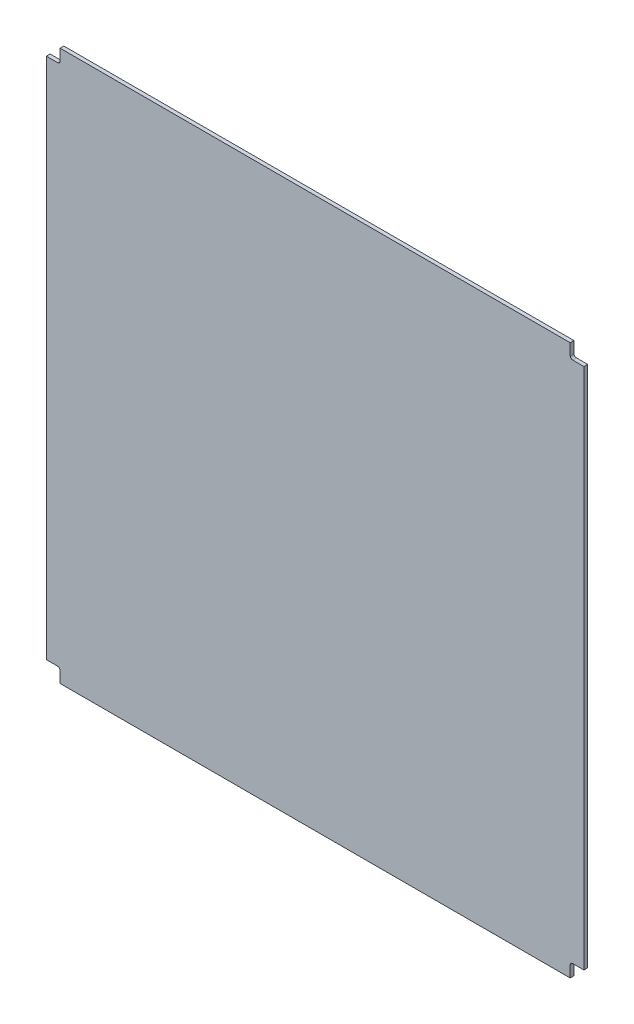
SolidWorks part; units mm, degrees
ref_plane "Front Plane" through (0, 0, 0) normal (0, 0, 1) x (1, 0, 0)
ref_plane "Top Plane" through (0, 0, 0) normal (0, 1, 0) x (1, 0, 0)
ref_plane "Right Plane" through (0, 0, 0) normal (1, 0, 0) x (0, 0, -1)
sketch "Sketch1" plane through (0, 0, 0) normal (0, 0, 1) x (1, 0, 0)
  line L0 (0, 427.6735) -> (0, 0) construction
  line L1 (0, 0) -> (427.6735, 0) construction
  line L2 (215, 209) -> (206, 209)
  line L3 (-215, 220) -> (215, 220)
  line L4 (-215, 220) -> (-215, -220)
  line L5 (-215, -220) -> (215, -220)
  line L6 (215, 220) -> (215, -220)
  line L7 (-215, 220) -> (-204, 220)
  line L8 (-215, 220) -> (-215, 209)
  line L9 (-215, 209) -> (-206, 209)
  line L10 (-204, 220) -> (-204, 211)
  line L11 (204, 220) -> (204, 211)
  line L12 (215, 220) -> (204, 220)
  line L13 (215, 220) -> (215, 209)
  line L14 (215, -220) -> (204, -220)
  line L15 (204, -220) -> (204, -211)
  line L16 (215, -209) -> (206, -209)
  line L17 (215, -220) -> (215, -209)
  line L18 (-215, -209) -> (-206, -209)
  line L19 (-204, -220) -> (-204, -211)
  line L20 (-215, -220) -> (-204, -220)
  line L21 (-215, -220) -> (-215, -209)
  arc A0 (-206, 209) -> (-204, 211) centre (-206, 211) ccw
  arc A1 (206, 209) -> (204, 211) centre (206, 211) cw
  arc A2 (206, -209) -> (204, -211) centre (206, -211) ccw
  arc A3 (-206, -209) -> (-204, -211) centre (-206, -211) cw
  point P13 (-204, 209)
  dimension "D5" = 2
  dimension "D1" = 440
  dimension "D2" = 430
  dimension "D3" = 11
  dimension "D4" = 11
extrude "Boss-Extrude1" add sketch "Sketch1" along normal blind 3 contours L18 A3 L19 L5 L15 A2 L16 L6 L2 A1 L11 L3 L10 A0 L9 L4
